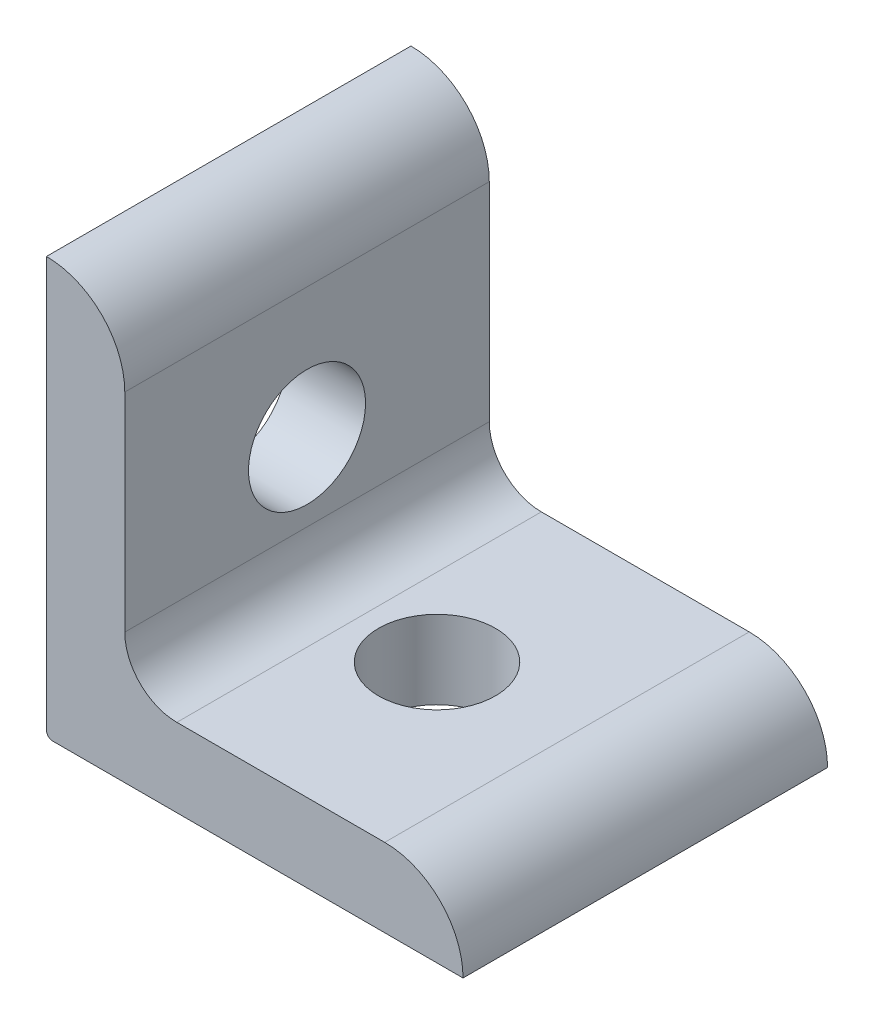
SolidWorks part; units mm, degrees
material "6105-T5"
ref_plane "Front Plane" through (0, 0, 0) normal (0, 0, 1) x (1, 0, 0)
ref_plane "Top Plane" through (0, 0, 0) normal (0, 1, 0) x (1, 0, 0)
ref_plane "Right Plane" through (0, 0, 0) normal (1, 0, 0) x (0, 0, -1)
ref_plane "Plane1" through (0, 0, -11.1125) normal (0, 0, -1) x (-1, 0, 0)
sketch "Sketch1" plane through (0, 0, -11.1125) normal (0, 0, -1) x (-1, 0, 0)
  line L0 (-25.4, 0) -> (0, 0)
  line L1 (0, 0) -> (0, 25.4)
  line L2 (-4.7752, 20.6248) -> (-4.7752, 4.7752)
  line L3 (-4.7752, 4.7752) -> (-20.6248, 4.7752)
  arc A0 (0, 25.4) -> (-4.7752, 20.6248) centre (0, 20.6248) ccw
  arc A1 (-20.6248, 4.7752) -> (-25.4, 0) centre (-20.6248, 0) ccw
extrude "Boss-Extrude1" add sketch "Sketch1" against normal mid plane 22.225
hole_wizard "Hole1" positions "Sketch3" profile "Sketch2" legacy end condition through all
sketch "Sketch3" plane through (0, 4.7752, 0) normal (0, 1, 0) x (-1, 0, 0)
  line L4 (0, -11.1125) -> (-12.7, -11.1125) construction
  line L5 (0, 0) -> (0, -22.225) construction
  point P0 (-12.7, -11.1125)
  dimension "D1" = 12.7
sketch "Sketch2" plane through (12.7, 4.7752, -11.1125) normal (1, 0, 0) x (0, 0, 1)
  line L0 (0, 0) -> (0, 4.7752)
  line L1 (0, 4.7752) -> (3.5687, 4.7752)
  line L2 (3.5687, 4.7752) -> (3.5687, 0)
  line L3 (3.5687, 0) -> (0, 0)
  line L4 (0, 110) -> (0, -10) construction
  dimension "Diameter" = 7.1374
  dimension "Depth" = 4.7752
hole_wizard "Hole2" positions "Sketch5" profile "Sketch4" legacy end condition through all
sketch "Sketch5" plane through (4.7752, 0, 0) normal (1, 0, 0) x (0, 0, -1)
  line L0 (11.1125, 12.7) -> (11.1125, 20.6248) construction
  line L1 (0, 20.6248) -> (22.225, 20.6248) construction
  line L3 (0, 25.4) -> (22.225, 25.4) construction
  point P0 (11.1125, 12.7)
  point P9 (11.1125, 25.4)
  dimension "D1" = 12.7
sketch "Sketch4" plane through (4.7752, 12.7, -11.1125) normal (0, 1, 0) x (0, 0, -1)
  line L0 (0, 0) -> (0, 4.7752)
  line L1 (0, 4.7752) -> (3.5687, 4.7752)
  line L2 (3.5687, 4.7752) -> (3.5687, 0)
  line L3 (3.5687, 0) -> (0, 0)
  line L4 (0, 110) -> (0, -10) construction
  dimension "Diameter" = 7.1374
  dimension "Depth" = 4.7752
fillet "Fillet1" radius 0.381 1 edges at (0, 0, -11.1125)
fillet "Fillet2" radius 3.175 1 edges at (4.7752, 4.7752, -11.1125)
